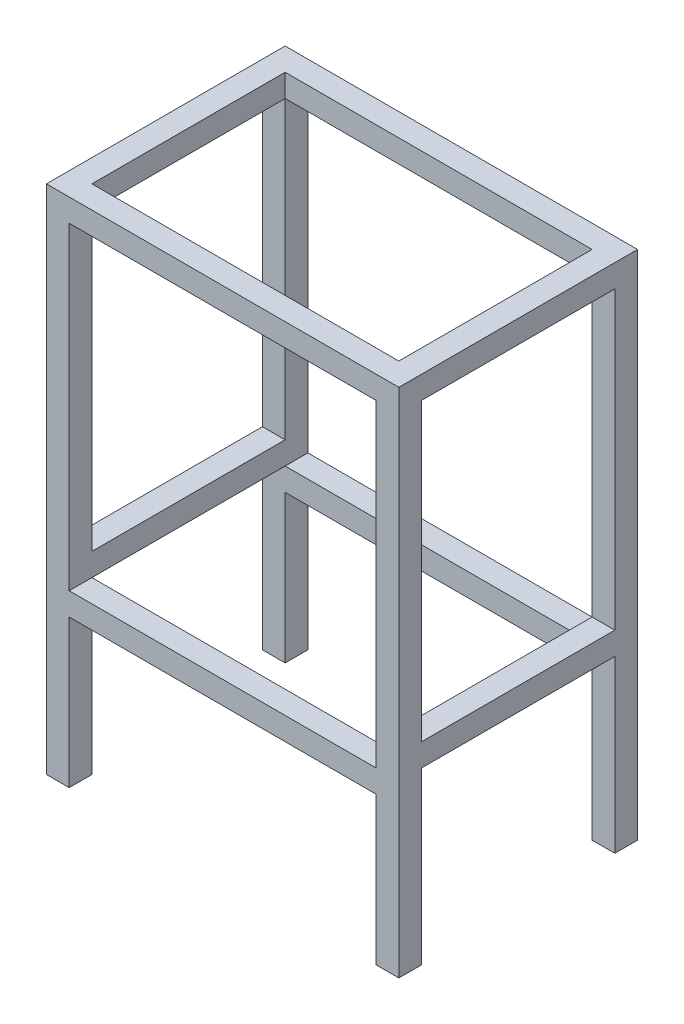
SolidWorks part; units mm, degrees
material "A286 铁基超合金"
ref_plane "前视基准面" through (0, 0, 0) normal (0, 0, 1) x (1, 0, 0)
ref_plane "上视基准面" through (0, 0, 0) normal (0, 1, 0) x (1, 0, 0)
ref_plane "右视基准面" through (0, 0, 0) normal (1, 0, 0) x (0, 0, -1)
other "Configuration Table"
sketch "草图1" plane through (0, 0, 0) normal (0, 1, 0) x (1, 0, 0)
  line L0 (-135, 85) -> (-135, -85)
  line L1 (-155, 105) -> (155, 105)
  line L2 (-155, 105) -> (-155, -105)
  line L3 (-155, -105) -> (155, -105)
  line L4 (155, 105) -> (155, -105)
  line L5 (-155, 105) -> (155, -105) construction
  line L6 (-155, -105) -> (155, 105) construction
  line L7 (-135, -85) -> (135, -85)
  line L8 (135, 85) -> (135, -85)
  line L9 (-135, 85) -> (135, 85)
  line L10 (0, -55) -> (0, 55) construction
  point P0 (0, 0)
  dimension "D1" = 310
  dimension "D2" = 210
  dimension "D3" = 20
extrude "凸台-拉伸1" add sketch "草图1" along normal blind 450 contours L0 L7 L8 L9 | L2 L3 L4 L1
ref_plane "基准面1" through (165, 0, 0) normal (1, 0, 0) x (0, 0, -1)
sketch "草图8" plane through (155, 0, 0) normal (1, 0, 0) x (0, 0, -1)
  line L0 (-105, 450) -> (-105, 0)
  line L1 (-105, 450) -> (-85, 450)
  line L2 (-105, 450) -> (-105, 430)
  line L3 (-105, 430) -> (-85, 430)
  line L4 (-85, 450) -> (-85, 430)
  line L5 (-105, 0) -> (-85, 0)
  line L6 (-85, 0) -> (-85, 100)
  line L7 (-85, 100) -> (-85, 150)
  line L8 (-85, 150) -> (85, 150)
  line L9 (85, 150) -> (85, 0)
  line L10 (105, 0) -> (-105, 0) construction
  line L11 (85, 0) -> (105, 0)
  line L12 (105, 0) -> (105, 450)
  line L13 (105, 450) -> (105, 0) construction
  line L14 (105, 450) -> (-105, 450)
  line L15 (85, 170) -> (-85, 170)
  line L16 (-85, 170) -> (-85, 430)
  line L17 (-85, 430) -> (85, 430)
  line L18 (85, 430) -> (85, 170)
  line L19 (-85, 0) -> (85, 0)
  line L20 (-85, 0) -> (85, 0)
  dimension "D1" = 20
  dimension "D2" = 20
  dimension "D3" = 20
extrude "切除-拉伸3" cut sketch "草图8" against normal blind 310 contours L17 L18 L15 L16
sketch "草图11" plane through (155, 0, 0) normal (1, 0, 0) x (0, 0, -1)
  line L0 (85, 170) -> (85, 150)
  line L1 (85, 150) -> (-85, 150)
  line L2 (-85, 150) -> (-85, 0)
  line L3 (-85, 0) -> (85, 0)
  line L4 (85, 0) -> (85, 150)
extrude "切除-拉伸4" cut sketch "草图11" against normal blind 310 contours L1 L2 L3 L4
ref_plane "基准面2" through (0, 0, 115) normal (0, 0, 1) x (1, 0, 0)
sketch "草图13" plane through (0, 0, 105) normal (0, 0, 1) x (1, 0, 0)
  line L1 (-135, 0) -> (-135, 130)
  line L2 (-155, 0) -> (155, 0) construction
  line L3 (-135, 130) -> (135, 130)
  line L4 (135, 130) -> (135, 0)
  line L5 (135, 0) -> (-135, 0)
  point P2 (0, 0)
extrude "切除-拉伸5" cut sketch "草图13" against normal through all
sketch "草图14" plane through (0, 0, 115) normal (0, 0, 1) x (1, 0, 0)
  line L0 (-135, 150) -> (-135, 430)
  line L1 (-135, 150) -> (135, 150)
  line L2 (-135, 430) -> (135, 430)
  line L3 (135, 430) -> (135, 150)
extrude "切除-拉伸6" cut sketch "草图14" against normal through all
